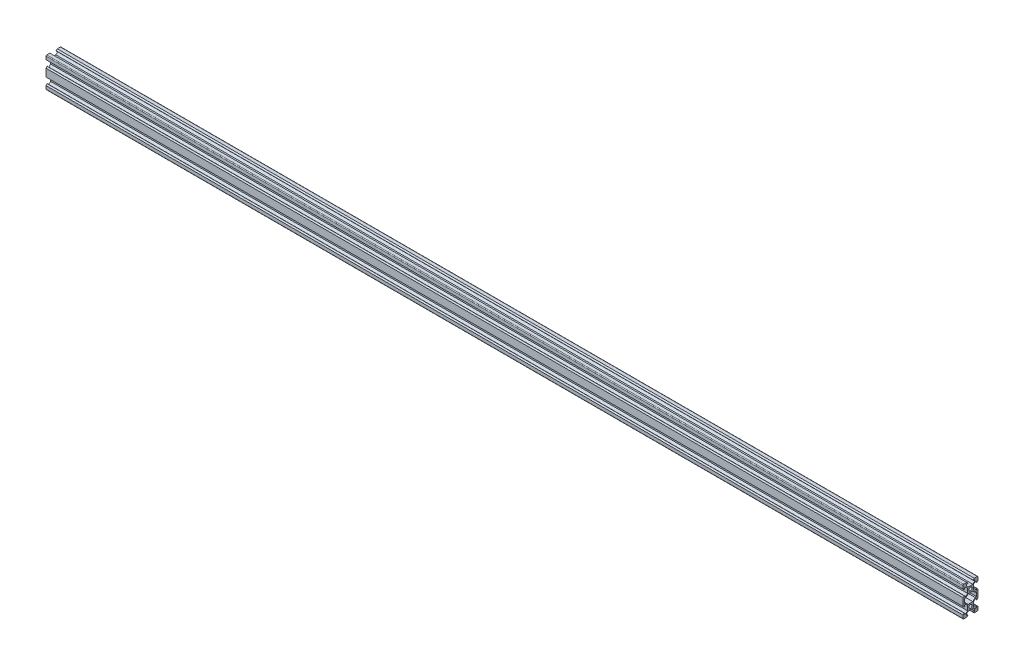
SolidWorks part; units mm, degrees
ref_plane "Front Plane" through (0, 0, 0) normal (0, 0, 1) x (1, 0, 0)
ref_plane "Top Plane" through (0, 0, 0) normal (0, 1, 0) x (1, 0, 0)
ref_plane "Right Plane" through (0, 0, 0) normal (1, 0, 0) x (0, 0, -1)
sketch "Sketch1" plane through (0, 0, 0) normal (0, 1, 0) x (1, 0, 0)
  line L1 (-609.6, 0) -> (609.6, 0)
  point P8 (0, 0)
  dimension "D2" = 1219.2
ref_plane "Plane1" through (-609.6, 0, 0) normal (1, 0, 0) x (0, 0, -1)
other "Vslot2040 2040(2)"
ref_plane "Plane3" through (-609.6, 0, 0) normal (1, 0, 0) x (0, 0, -1)
sketch "Sketch12" plane through (-609.6, 0, 0) normal (1, 0, 0) x (0, 0, -1)
  line L12 (3.125, 6.1) -> (6.275, 2.95)
  line L13 (6.275, 2.95) -> (8.2, 2.95)
  line L14 (8.2, 2.95) -> (8.2, -2.95)
  line L15 (8.2, -2.95) -> (6.275, -2.95)
  line L16 (3.125, -6.1) -> (6.275, -2.95)
  line L17 (3.125, -6.1) -> (-3.125, -6.1)
  line L18 (-3.125, -6.1) -> (-6.275, -2.95)
  line L19 (-8.2, -2.95) -> (-6.275, -2.95)
  line L20 (-8.2, 2.95) -> (-8.2, -2.95)
  line L21 (-6.275, 2.95) -> (-8.2, 2.95)
  line L22 (-3.125, 6.1) -> (-6.275, 2.95)
  line L23 (3.125, 6.1) -> (-3.125, 6.1)
  line L128 (5.5, -18.2) -> (3.6078, -18.2)
  line L129 (3.4664, -18.5414) -> (4.925, -20)
  line L130 (4.925, -20) -> (9, -20)
  line L131 (10, -19) -> (10, -14.925)
  line L132 (10, -14.925) -> (8.5414, -13.4664)
  line L133 (8.2, -13.6078) -> (8.2, -15.5)
  line L134 (8.2, -15.5) -> (6.275, -15.5)
  line L135 (6.275, -15.5) -> (3.9, -13.125)
  line L136 (3.9, -13.125) -> (3.9, -6.875)
  line L137 (3.9, -6.875) -> (6.275, -4.5)
  line L138 (6.275, -4.5) -> (8.2, -4.5)
  line L139 (8.2, -4.5) -> (8.2, -6.3922)
  line L140 (8.5414, -6.5336) -> (10, -5.075)
  line L141 (10, -5.075) -> (10, 5.075)
  line L142 (10, 5.075) -> (8.5414, 6.5336)
  line L143 (8.2, 6.3922) -> (8.2, 4.5)
  line L144 (8.2, 4.5) -> (6.275, 4.5)
  line L145 (6.275, 4.5) -> (3.9, 6.875)
  line L146 (3.9, 6.875) -> (3.9, 13.125)
  line L147 (3.9, 13.125) -> (6.275, 15.5)
  line L148 (6.275, 15.5) -> (8.2, 15.5)
  line L149 (8.2, 15.5) -> (8.2, 13.6078)
  line L150 (8.5414, 13.4664) -> (10, 14.925)
  line L151 (10, 14.925) -> (10, 19)
  line L152 (9, 20) -> (4.925, 20)
  line L153 (4.925, 20) -> (3.4664, 18.5414)
  line L154 (3.6078, 18.2) -> (5.5, 18.2)
  line L155 (5.5, 18.2) -> (5.5, 16.275)
  line L156 (5.5, 16.275) -> (3.125, 13.9)
  line L157 (3.125, 13.9) -> (-3.125, 13.9)
  line L158 (-3.125, 13.9) -> (-5.5, 16.275)
  line L159 (-5.5, 16.275) -> (-5.5, 18.2)
  line L160 (-5.5, 18.2) -> (-3.6078, 18.2)
  line L161 (-3.4664, 18.5414) -> (-4.925, 20)
  line L162 (-4.925, 20) -> (-9, 20)
  line L163 (-10, 19) -> (-10, 14.925)
  line L164 (-10, 14.925) -> (-8.5414, 13.4664)
  line L165 (-8.2, 13.6078) -> (-8.2, 15.5)
  line L166 (-8.2, 15.5) -> (-6.275, 15.5)
  line L167 (-6.275, 15.5) -> (-3.9, 13.125)
  line L168 (-3.9, 13.125) -> (-3.9, 6.875)
  line L169 (-3.9, 6.875) -> (-6.275, 4.5)
  line L170 (-6.275, 4.5) -> (-8.2, 4.5)
  line L171 (-8.2, 4.5) -> (-8.2, 6.3922)
  line L172 (-8.5414, 6.5336) -> (-10, 5.075)
  line L173 (-10, 5.075) -> (-10, -5.075)
  line L174 (-10, -5.075) -> (-8.5414, -6.5336)
  line L175 (-8.2, -6.3922) -> (-8.2, -4.5)
  line L176 (-8.2, -4.5) -> (-6.275, -4.5)
  line L177 (-6.275, -4.5) -> (-3.9, -6.875)
  line L178 (-3.9, -6.875) -> (-3.9, -13.125)
  line L179 (-3.9, -13.125) -> (-6.275, -15.5)
  line L180 (-6.275, -15.5) -> (-8.2, -15.5)
  line L181 (-8.2, -15.5) -> (-8.2, -13.6078)
  line L182 (-8.5414, -13.4664) -> (-10, -14.925)
  line L183 (-10, -14.925) -> (-10, -19)
  line L184 (-9, -20) -> (-4.925, -20)
  line L185 (-4.925, -20) -> (-3.4664, -18.5414)
  line L186 (-3.6078, -18.2) -> (-5.5, -18.2)
  line L187 (-5.5, -18.2) -> (-5.5, -16.275)
  line L188 (-5.5, -16.275) -> (-3.125, -13.9)
  line L189 (-3.125, -13.9) -> (3.125, -13.9)
  line L190 (3.125, -13.9) -> (5.5, -16.275)
  line L191 (5.5, -16.275) -> (5.5, -18.2)
  circle A2 centre (0, -10) radius 2.1
  circle A3 centre (0, 10) radius 2.1
  arc A32 (3.6078, -18.2) -> (3.4664, -18.5414) centre (3.6078, -18.4) ccw
  arc A33 (9, -20) -> (10, -19) centre (9, -19) ccw
  arc A34 (8.5414, -13.4664) -> (8.2, -13.6078) centre (8.4, -13.6078) ccw
  arc A35 (8.2, -6.3922) -> (8.5414, -6.5336) centre (8.4, -6.3922) ccw
  arc A36 (8.5414, 6.5336) -> (8.2, 6.3922) centre (8.4, 6.3922) ccw
  arc A37 (8.2, 13.6078) -> (8.5414, 13.4664) centre (8.4, 13.6078) ccw
  arc A38 (10, 19) -> (9, 20) centre (9, 19) ccw
  arc A39 (3.4664, 18.5414) -> (3.6078, 18.2) centre (3.6078, 18.4) ccw
  arc A40 (-3.6078, 18.2) -> (-3.4664, 18.5414) centre (-3.6078, 18.4) ccw
  arc A41 (-9, 20) -> (-10, 19) centre (-9, 19) ccw
  arc A42 (-8.5414, 13.4664) -> (-8.2, 13.6078) centre (-8.4, 13.6078) ccw
  arc A43 (-8.2, 6.3922) -> (-8.5414, 6.5336) centre (-8.4, 6.3922) ccw
  arc A44 (-8.5414, -6.5336) -> (-8.2, -6.3922) centre (-8.4, -6.3922) ccw
  arc A45 (-8.2, -13.6078) -> (-8.5414, -13.4664) centre (-8.4, -13.6078) ccw
  arc A46 (-10, -19) -> (-9, -20) centre (-9, -19) ccw
  arc A47 (-3.4664, -18.5414) -> (-3.6078, -18.2) centre (-3.6078, -18.4) ccw
  point P43 (0, 0)
